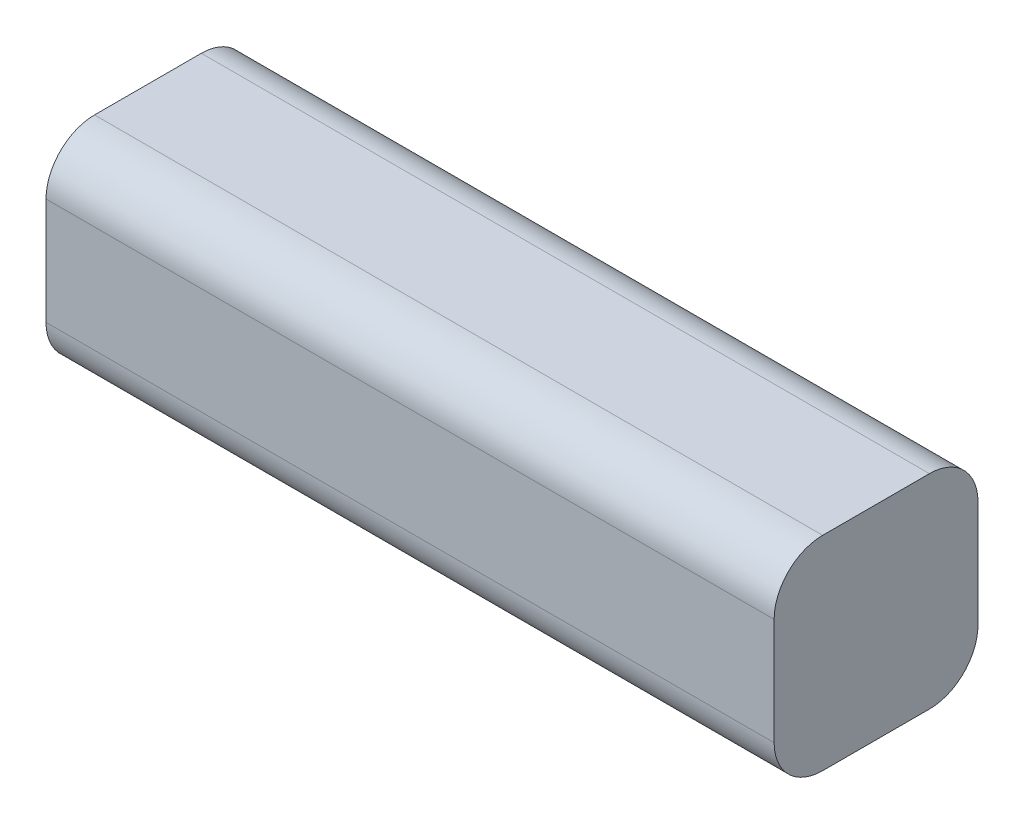
SolidWorks part; units mm, degrees
ref_plane "前视基准面" through (0, 0, 0) normal (0, 0, 1) x (1, 0, 0)
ref_plane "上视基准面" through (0, 0, 0) normal (0, 1, 0) x (1, 0, 0)
ref_plane "右视基准面" through (0, 0, 0) normal (1, 0, 0) x (0, 0, -1)
sketch "草图1" plane through (0, 0, 0) normal (0, 1, 0) x (1, 0, 0)
  line L0 (0, 0) -> (150, 0)
  line L1 (150, 0) -> (150, 42)
  line L2 (150, 42) -> (0, 42)
  line L3 (0, 42) -> (0, 0)
  dimension "D1" = 42
  dimension "D2" = 150
extrude "凸台-拉伸1" add sketch "草图1" along normal blind 42
fillet "圆角1" radius 10 4 edges at (75, 42, 0) (75, 0, 0) (75, 0, -42) (75, 42, -42)
sketch "草图2" plane through (0, 42, 0) normal (0, 1, 0) x (1, 0, 0)
  text T0 "<b>3500MAH</b>" font "黑体" height in points 36
